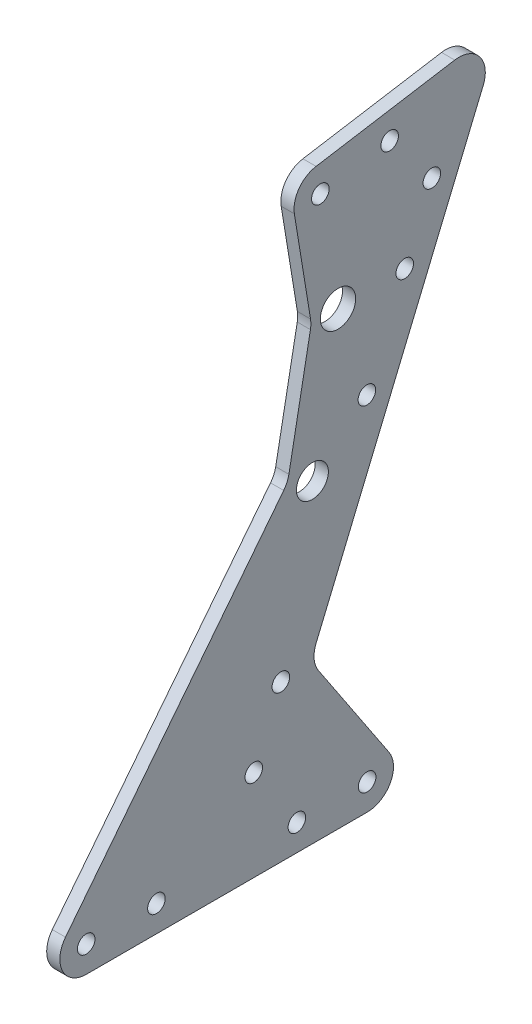
SolidWorks part; units mm, degrees
ref_plane "Front Plane" through (0, 0, 0) normal (0, 0, 1) x (1, 0, 0)
ref_plane "Top Plane" through (0, 0, 0) normal (0, 1, 0) x (1, 0, 0)
ref_plane "Right Plane" through (0, 0, 0) normal (1, 0, 0) x (0, 0, -1)
sketch "Sketch2" plane through (0, 0, 0) normal (1, 0, 0) x (0, 0, -1)
  line L0 (-1136.4452, 150.1825) -> (-1167.6402, 197.047) construction
  line L1 (-1253.4642, 150.789) -> (-1171.6662, 254.9058) construction
  line L2 (-1245.9743, 135.3796) -> (-1144.3743, 135.3796) construction
  line L3 (-1136.4452, 150.1825) -> (-1167.6402, 197.047)
  line L4 (-1253.4642, 150.789) -> (-1171.6662, 254.9058)
  line L5 (-1245.9743, 135.3796) -> (-1144.3743, 135.3796)
  line L6 (-1166.7822, 188.0932) -> (-1112.1825, 318.6104) construction
  line L7 (-1095.7438, 357.9062) -> (-1112.1825, 318.6104) construction
  line L8 (-1137.7756, 350.9984) -> (-1095.7438, 357.9062) construction
  line L9 (-1162.8393, 346.8792) -> (-1137.7756, 350.9984) construction
  line L10 (-1164.3072, 296.7728) -> (-1170.6955, 335.9473) construction
  line L11 (-1164.2672, 300.0665) -> (-1173.5371, 250.7821) construction
  line L12 (-1166.7822, 188.0932) -> (-1112.1825, 318.6104)
  line L13 (-1095.7438, 357.9062) -> (-1112.1825, 318.6104)
  line L14 (-1137.7756, 350.9984) -> (-1095.7438, 357.9062)
  line L15 (-1162.8393, 346.8792) -> (-1137.7756, 350.9984)
  line L16 (-1164.3072, 296.7728) -> (-1170.6955, 335.9473)
  line L17 (-1164.2672, 300.0665) -> (-1173.5371, 250.7821)
  circle A0 centre (-1144.3743, 144.9046) radius 9.525 construction
  circle A1 centre (-1245.9743, 144.9046) radius 9.525 construction
  arc A2 (-1144.3743, 135.3796) -> (-1136.4452, 150.1825) centre (-1144.3743, 144.9046) ccw
  arc A3 (-1253.4642, 150.789) -> (-1245.9743, 135.3796) centre (-1245.9743, 144.9046) ccw
  circle A4 centre (-1161.2946, 337.4803) radius 9.525 construction
  arc A5 (-1162.8393, 346.8792) -> (-1170.6955, 335.9473) centre (-1161.2946, 337.4803) ccw
  circle A6 centre (-1164.1763, 249.0214) radius 5.7813 construction
  circle A7 centre (-1164.1763, 249.0214) radius 5.7813
  circle A8 centre (-1154.9064, 298.3059) radius 6.3821 construction
  circle A9 centre (-1154.9064, 298.3059) radius 6.3821
  circle A10 centre (-1120.9696, 322.2864) radius 3.175 construction
  circle A11 centre (-1130.7721, 298.8541) radius 3.175 construction
  circle A12 centre (-1136.2309, 341.5995) radius 3.175 construction
  circle A13 centre (-1161.2946, 337.4803) radius 3.175 construction
  circle A14 centre (-1120.9696, 322.2864) radius 3.175
  circle A15 centre (-1130.7721, 298.8541) radius 3.175
  circle A16 centre (-1136.2309, 341.5995) radius 3.175
  circle A17 centre (-1161.2946, 337.4803) radius 3.175
  circle A18 centre (-1245.9743, 144.9046) radius 3.175 construction
  circle A19 centre (-1220.5743, 144.9046) radius 3.175 construction
  circle A20 centre (-1185.3718, 168.3368) radius 3.175 construction
  circle A21 centre (-1144.3743, 144.9046) radius 3.175 construction
  circle A22 centre (-1169.7743, 144.9046) radius 3.175 construction
  circle A23 centre (-1245.9743, 144.9046) radius 3.175
  circle A24 centre (-1220.5743, 144.9046) radius 3.175
  circle A25 centre (-1185.3718, 168.3368) radius 3.175
  circle A26 centre (-1144.3743, 144.9046) radius 3.175
  circle A27 centre (-1169.7743, 144.9046) radius 3.175
  circle A28 centre (-1175.5693, 191.7691) radius 3.175 construction
  circle A29 centre (-1175.5693, 191.7691) radius 3.175
  circle A30 centre (-1144.4658, 266.1201) radius 3.175 construction
  circle A31 centre (-1144.4658, 266.1201) radius 3.175
extrude "Boss-Extrude1" add sketch "Sketch2" along normal up to vertex (17.2911 mm away) from vertex at 12.5286
fillet "Fillet1" radius 9.525 4 edges at (14.9099, 192.7999, 1164.8132) (14.9099, 253.0729, 1173.1063) (14.9099, 298.4232, 1164.5763) (14.9099, 357.9062, 1095.7438)
